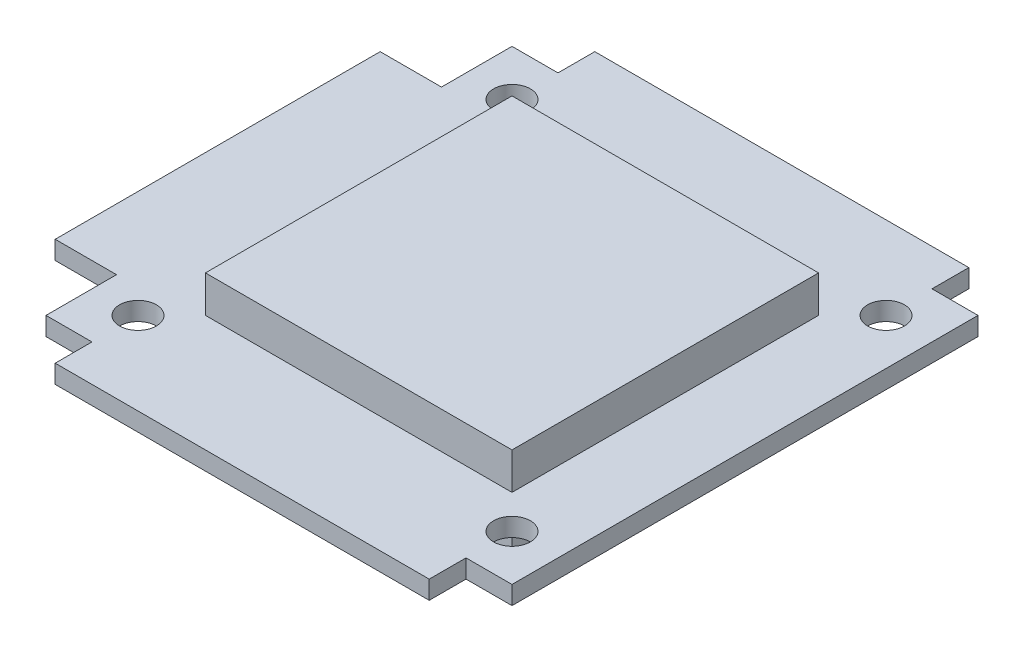
SolidWorks part; units mm, degrees
ref_plane "前视基准面" through (0, 0, 0) normal (0, 0, 1) x (1, 0, 0)
ref_plane "上视基准面" through (0, 0, 0) normal (0, 1, 0) x (1, 0, 0)
ref_plane "右视基准面" through (0, 0, 0) normal (1, 0, 0) x (0, 0, -1)
other "Configuration Table"
sketch "草图1" plane through (0, 0, 0) normal (0, 1, 0) x (1, 0, 0)
  line L1 (-19, -19) -> (19, -19)
  line L2 (-19, -19) -> (-19, 19)
  line L3 (-19, 19) -> (19, 19)
  line L4 (19, -19) -> (19, 19)
  line L5 (-19, -19) -> (19, 19) construction
  line L6 (-19, 19) -> (19, -19) construction
  circle A0 centre (-15.25, 15.25) radius 1.5
  circle A1 centre (15.25, 15.25) radius 1.5
  circle A2 centre (15.25, -15.25) radius 1.5
  circle A3 centre (-15.25, -15.25) radius 1.5
  point P0 (0, 0)
  point P17 (0, 0)
  dimension "D3" = 3
  dimension "D4" = 15.25
  dimension "D5" = 4
  dimension "D1" = 38
  dimension "D2" = 38
extrude "凸台-拉伸1" add sketch "草图1" along normal blind 1.5
sketch "草图2" plane through (0, 0, 0) normal (0, -1, 0) x (1, 0, 0)
  line L0 (-19, -19) -> (-19, 19) construction
  line L1 (-19, 13.25) -> (-24, 13.25)
  line L2 (-19, 13.25) -> (-19, -13.25)
  line L3 (-19, -13.25) -> (-24, -13.25)
  line L4 (-24, 13.25) -> (-24, -13.25)
  line L10 (19, -19) -> (-19, -19) construction
  line L11 (-15.25, -19) -> (15.25, -19)
  line L12 (-15.25, -19) -> (-15.25, -22)
  line L13 (-15.25, -22) -> (15.25, -22)
  line L14 (15.25, -19) -> (15.25, -22)
  line L15 (-1000, 0) -> (49000, 0) construction
  line L16 (-15.25, 22) -> (15.25, 22)
  line L17 (15.25, 19) -> (15.25, 22)
  line L18 (-15.25, 19) -> (15.25, 19)
  line L19 (-15.25, 19) -> (-15.25, 22)
  circle A0 centre (-15.25, -15.25) radius 1.5 construction
  circle A1 centre (15.25, -15.25) radius 1.5 construction
  circle A3 centre (-15.25, 15.25) radius 1.5 construction
  point P18 (-15.25, -20.5)
  dimension "D1" = 3
  dimension "D2" = 0
  dimension "D3" = 0
  dimension "D4" = 2
  dimension "D5" = 2
  dimension "D7" = 5
extrude "凸台-拉伸2" add sketch "草图2" against normal blind 1.5
sketch "草图3" plane through (0, 1.5, 0) normal (0, 1, 0) x (1, 0, 0)
  line L1 (-12.5, -12.5) -> (12.5, -12.5)
  line L2 (-12.5, -12.5) -> (-12.5, 12.5)
  line L3 (-12.5, 12.5) -> (12.5, 12.5)
  line L4 (12.5, -12.5) -> (12.5, 12.5)
  line L5 (-12.5, -12.5) -> (12.5, 12.5) construction
  line L6 (-12.5, 12.5) -> (12.5, -12.5) construction
  point P0 (0, 0)
  dimension "D1" = 25
  dimension "D2" = 25
extrude "凸台-拉伸3" add sketch "草图3" along normal blind 3 and the other way blind 4.5
